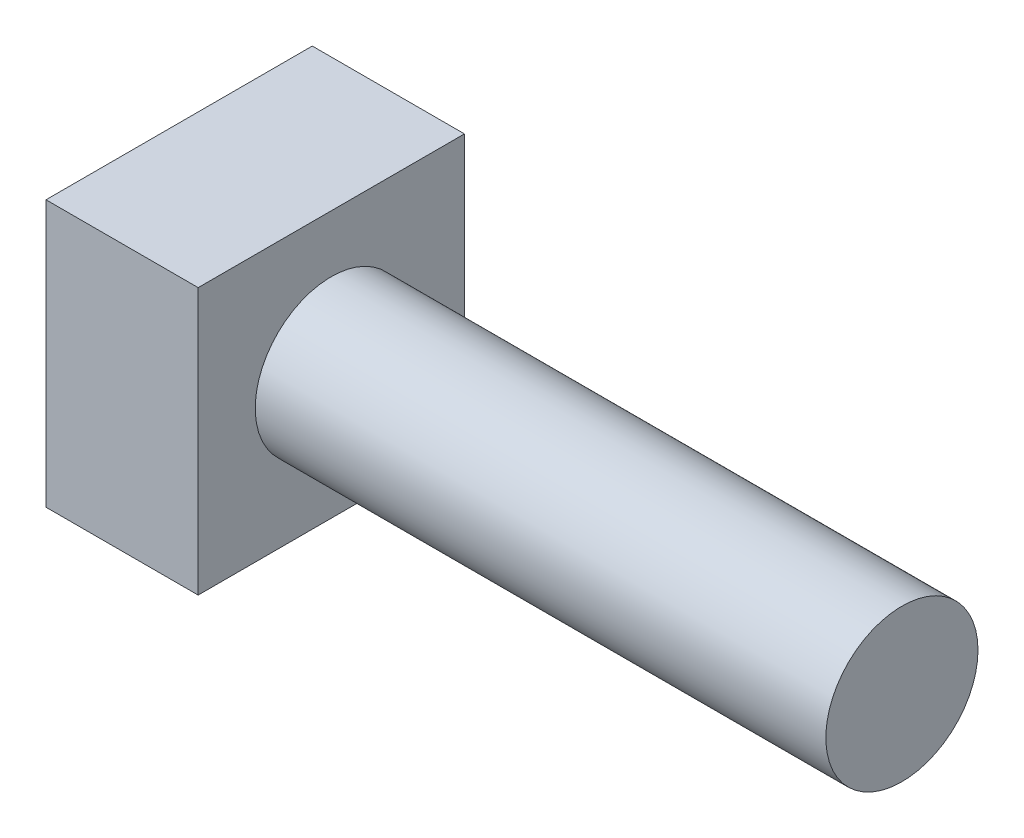
SolidWorks part; units mm, degrees
ref_plane "Front Plane" through (0, 0, 0) normal (0, 0, 1) x (1, 0, 0)
ref_plane "Top Plane" through (0, 0, 0) normal (0, 1, 0) x (1, 0, 0)
ref_plane "Right Plane" through (0, 0, 0) normal (1, 0, 0) x (0, 0, -1)
sketch "Sketch3" plane through (0, 0, 0) normal (1, 0, 0) x (0, 0, -1)
  line L1 (-3.5, 3.5) -> (3.5, 3.5)
  line L2 (-3.5, 3.5) -> (-3.5, -3.5)
  line L3 (-3.5, -3.5) -> (3.5, -3.5)
  line L4 (3.5, 3.5) -> (3.5, -3.5)
  line L5 (-3.5, 3.5) -> (3.5, -3.5) construction
  line L6 (-3.5, -3.5) -> (3.5, 3.5) construction
  point P0 (0, 0)
  dimension "D1" = 7
  dimension "D2" = 7
extrude "Boss-Extrude2" add sketch "Sketch3" along normal blind 4
sketch "Sketch4" plane through (4, 0, 0) normal (1, 0, 0) x (0, 0, -1)
  circle A0 centre (0, 0) radius 2
extrude "Boss-Extrude3" add sketch "Sketch4" along normal blind 15
